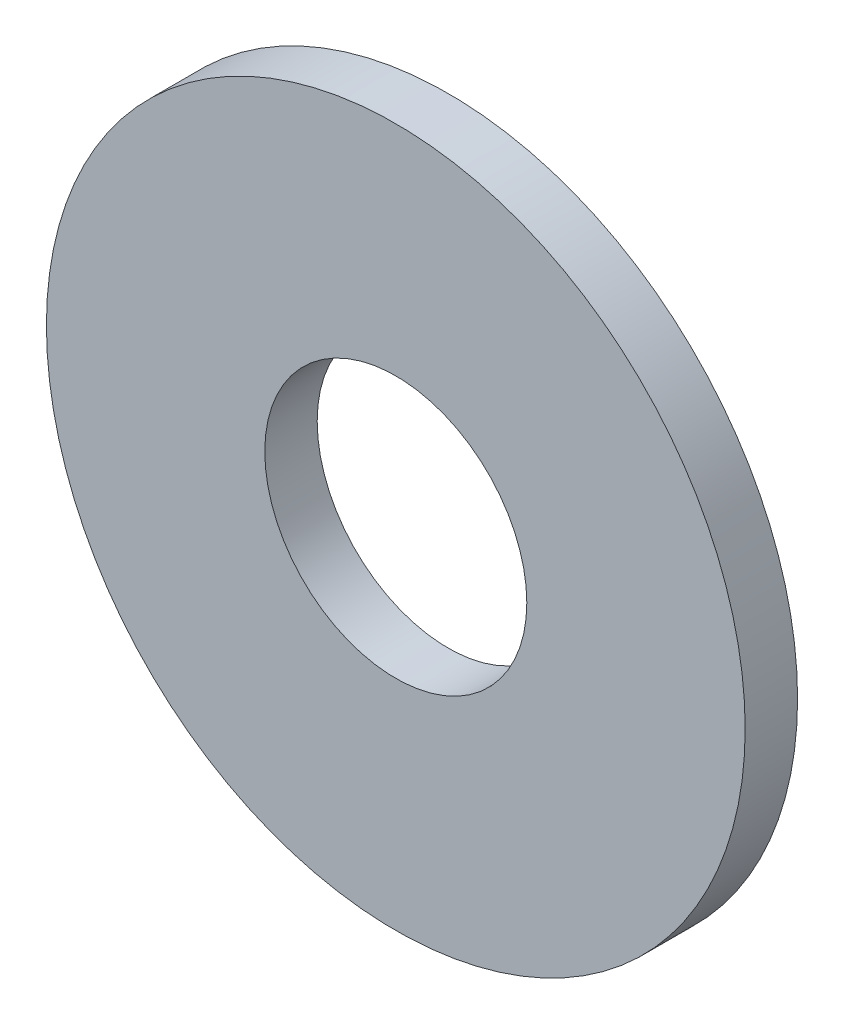
SolidWorks part; units mm, degrees
ref_plane "前视基准面" through (0, 0, 0) normal (0, 0, 1) x (1, 0, 0)
ref_plane "上视基准面" through (0, 0, 0) normal (0, 1, 0) x (1, 0, 0)
ref_plane "右视基准面" through (0, 0, 0) normal (1, 0, 0) x (0, 0, -1)
sketch "草图1" plane through (0, 0, 0) normal (0, 0, 1) x (1, 0, 0)
  circle A0 centre (0, 0) radius 3
  circle A1 centre (0, 0) radius 8
  dimension "D1" = 6
  dimension "D2" = 16
extrude "凸台-拉伸1" add sketch "草图1" along normal blind 1.2
